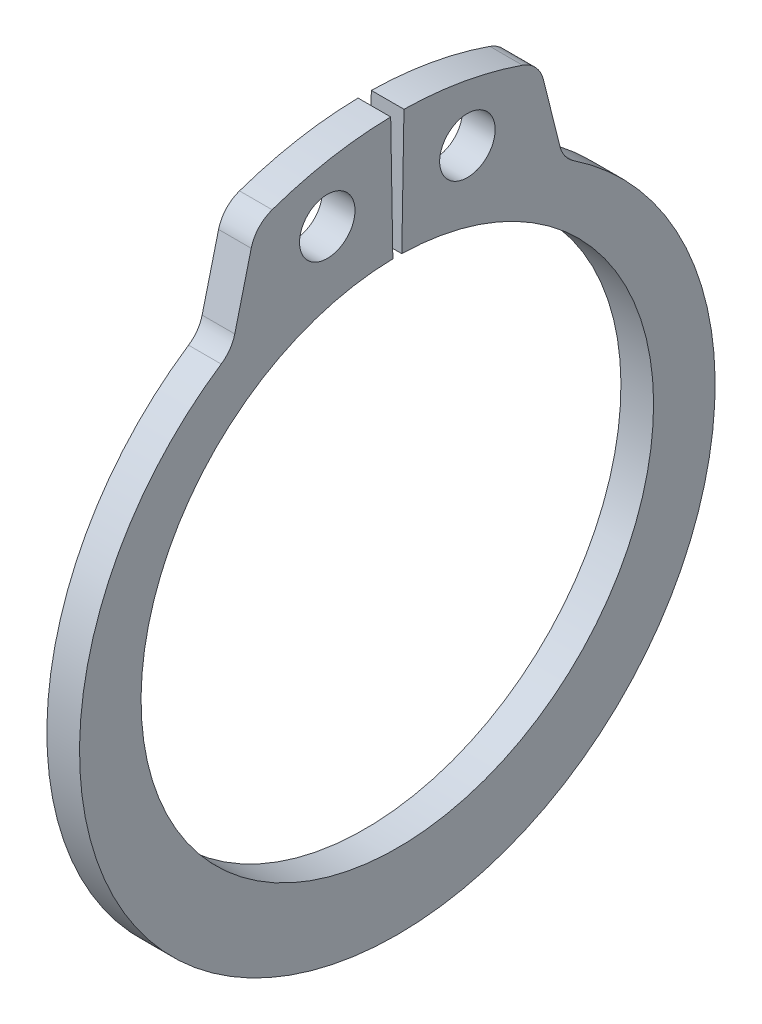
SolidWorks part; units mm, degrees
material "Cast Carbon Steel"
ref_plane "Front" through (0, 0, 0) normal (0, 0, 1) x (1, 0, 0)
ref_plane "Top" through (0, 0, 0) normal (0, 1, 0) x (1, 0, 0)
ref_plane "Right" through (0, 0, 0) normal (1, 0, 0) x (0, 0, -1)
sketch "Sketch1" plane through (0, 0, 0) normal (1, 0, 0) x (0, 0, -1)
  line L0 (0, 0) -> (0, 7.85) construction
  line L1 (-0.137, 7.8488) -> (-0.2033, 11.6482)
  line L2 (-0.2033, 11.6482) -> (-4.1563, 11.5792) construction
  line L3 (-4.1563, 11.5792) -> (-5.0756, 7.8921) construction
  line L4 (0.2033, 11.6482) -> (0.137, 7.8488)
  line L5 (0.2033, 11.6482) -> (4.1563, 11.5792) construction
  line L6 (4.1563, 11.5792) -> (5.0756, 7.8921) construction
  line L7 (-5.0756, 7.8921) -> (-4.2462, 6.6025) construction
  line L8 (5.0756, 7.8921) -> (4.2462, 6.6025) construction
  line L9 (0, -7.85) -> (0, -10.15) construction
  line L10 (-4.1563, 11.5792) -> (-0.137, 7.8488) construction
  line L11 (-7.85, 0) -> (7.85, 0) construction
  line L12 (0, 7.85) -> (0, 11.65) construction
  line L13 (4.3486, 10.808) -> (5.0756, 7.8921)
  line L14 (-4.3486, 10.808) -> (-5.0756, 7.8921)
  circle A0 centre (0, 0) radius 7.85 construction
  arc A1 (-0.137, 7.8488) -> (0.137, 7.8488) centre (0, 0) ccw
  circle A2 centre (0, -0.415) radius 9.735 construction
  circle A4 centre (-2.1466, 9.714) radius 0.85
  circle A5 centre (2.1466, 9.714) radius 0.85
  arc A6 (-5.0756, 7.8921) -> (5.0756, 7.8921) centre (0, -0.415) ccw
  arc A7 (0.2033, 11.6482) -> (4.3486, 10.808) centre (0, 0) cw
  arc A8 (-0.2033, 11.6482) -> (-4.3486, 10.808) centre (0, 0) ccw
  dimension "A" = 15.7
  dimension "Hole" = 1.7
  dimension "Smin" = 1.5333
  dimension "D1" = 75
  dimension "Angle" = 1
  dimension "H" = 3.8
extrude "Extrude1" add sketch "Sketch1" along normal mid plane 1
fillet "Fillet1" radius 1 4 edges at (0, 7.8921, 5.0756) (0, 10.808, 4.3486) (0, 10.808, -4.3486) (0, 7.8921, -5.0756)
sketch "Sketch2" plane through (0, 0, 0) normal (0, 0, 1) x (1, 0, 0)
  line L0 (-2.75, 0) -> (8.25, 0)
  line L1 (8.25, 0) -> (8.25, -8.5)
  line L2 (-2.75, 0) -> (-2.75, -8.1)
  line L3 (8.25, -8.5) -> (0.55, -8.5)
  line L4 (0.55, -8.5) -> (0.55, -8.1)
  line L5 (0.55, -8.1) -> (-0.55, -8.1)
  line L6 (-0.55, -8.1) -> (-0.55, -8.5)
  line L7 (-0.55, -8.5) -> (-2.75, -8.5) construction
  line L8 (-2.75, -8.5) -> (-2.75, 0) construction
  line L9 (0, -8.1) -> (0, 0) construction
  line L10 (8.25, 0) -> (14.0551, 0) construction
  line L11 (-2.75, -8.1) -> (-2.35, -8.5)
  line L12 (-2.35, -8.5) -> (-0.55, -8.5)
  dimension "D2" = 11
  dimension "D3" = 2.75
  dimension "D1" = 45
revolve "Revolve1" [suppressed] add sketch "Sketch2" angle 360 about L10
equation "\"D2@Sketch2\" = \"W@Sketch2\"*10"
equation "\"D3@Sketch2\" = \"D2@Sketch2\"/4"
equation "\"Smin@Sketch1\" = \"Smax@Sketch1\"/1.5"
equation "\"D1@Fillet1\" = \"D1@Extrude1\""
